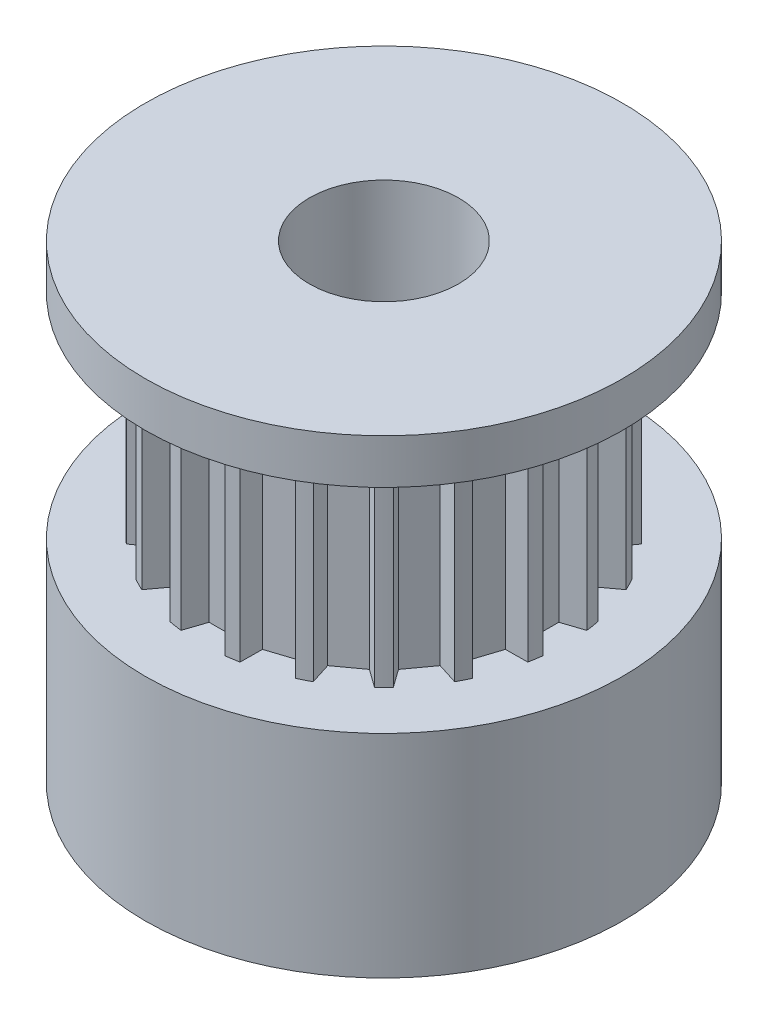
SolidWorks part; units mm, degrees
ref_plane "Front Plane" through (0, 0, 0) normal (0, 0, 1) x (1, 0, 0)
ref_plane "Top Plane" through (0, 0, 0) normal (0, 1, 0) x (1, 0, 0)
ref_plane "Right Plane" through (0, 0, 0) normal (1, 0, 0) x (0, 0, -1)
sketch "Sketch1" plane through (0, 0, 0) normal (0, 1, 0) x (1, 0, 0)
  circle A0 centre (0, 0) radius 8
extrude "Boss-Extrude1" add sketch "Sketch1" along normal blind 7.1
sketch "Sketch2" plane through (0, 7.1, 0) normal (0, 1, 0) x (1, 0, 0)
  circle A0 centre (0, 0) radius 6.11
extrude "Boss-Extrude2" add sketch "Sketch2" along normal blind 7.14
sketch "Sketch5" plane through (0, 0, 0) normal (0, -1, 0) x (1, 0, 0)
  circle A0 centre (0, 0) radius 2.5
extrude "Cut-Extrude2" cut sketch "Sketch5" against normal blind 16
sketch "Sketch7" plane through (0, 14.24, 0) normal (0, 1, 0) x (1, 0, 0)
  line L0 (0, 6.86) -> (0, 5.36) construction
  line L1 (-0.5, 5.36) -> (0.5, 5.36)
  line L2 (-1, 6.86) -> (1, 6.86)
  line L3 (-1, 6.86) -> (-0.5, 5.36)
  line L4 (1, 6.86) -> (0.5, 5.36)
  line L5 (0, 0) -> (0, 2.5) construction
  line L6 (3.0709, 6.2152) -> (2.1319, 4.9432)
  line L7 (1.1808, 5.2522) -> (2.1319, 4.9432)
  line L8 (1.1688, 6.8333) -> (1.1808, 5.2522)
  line L9 (1.1688, 6.8333) -> (3.0709, 6.2152)
  line L10 (4.8412, 4.9621) -> (3.555, 4.0424)
  line L11 (2.746, 4.6302) -> (3.555, 4.0424)
  line L12 (3.2232, 6.1376) -> (2.746, 4.6302)
  line L13 (3.2232, 6.1376) -> (4.8412, 4.9621)
  line L14 (6.1376, 3.2232) -> (4.6302, 2.746)
  line L15 (4.0424, 3.555) -> (4.6302, 2.746)
  line L16 (4.9621, 4.8412) -> (4.0424, 3.555)
  line L17 (4.9621, 4.8412) -> (6.1376, 3.2232)
  line L18 (6.8333, 1.1688) -> (5.2522, 1.1808)
  line L19 (4.9432, 2.1319) -> (5.2522, 1.1808)
  line L20 (6.2152, 3.0709) -> (4.9432, 2.1319)
  line L21 (6.2152, 3.0709) -> (6.8333, 1.1688)
  line L22 (6.86, -1) -> (5.36, -0.5)
  line L23 (5.36, 0.5) -> (5.36, -0.5)
  line L24 (6.86, 1) -> (5.36, 0.5)
  line L25 (6.86, 1) -> (6.86, -1)
  line L26 (6.2152, -3.0709) -> (4.9432, -2.1319)
  line L27 (5.2522, -1.1808) -> (4.9432, -2.1319)
  line L28 (6.8333, -1.1688) -> (5.2522, -1.1808)
  line L29 (6.8333, -1.1688) -> (6.2152, -3.0709)
  line L30 (4.9621, -4.8412) -> (4.0424, -3.555)
  line L31 (4.6302, -2.746) -> (4.0424, -3.555)
  line L32 (6.1376, -3.2232) -> (4.6302, -2.746)
  line L33 (6.1376, -3.2232) -> (4.9621, -4.8412)
  line L34 (3.2232, -6.1376) -> (2.746, -4.6302)
  line L35 (3.555, -4.0424) -> (2.746, -4.6302)
  line L36 (4.8412, -4.9621) -> (3.555, -4.0424)
  line L37 (4.8412, -4.9621) -> (3.2232, -6.1376)
  line L38 (1.1688, -6.8333) -> (1.1808, -5.2522)
  line L39 (2.1319, -4.9432) -> (1.1808, -5.2522)
  line L40 (3.0709, -6.2152) -> (2.1319, -4.9432)
  line L41 (3.0709, -6.2152) -> (1.1688, -6.8333)
  line L42 (-1, -6.86) -> (-0.5, -5.36)
  line L43 (0.5, -5.36) -> (-0.5, -5.36)
  line L44 (1, -6.86) -> (0.5, -5.36)
  line L45 (1, -6.86) -> (-1, -6.86)
  line L46 (-3.0709, -6.2152) -> (-2.1319, -4.9432)
  line L47 (-1.1808, -5.2522) -> (-2.1319, -4.9432)
  line L48 (-1.1688, -6.8333) -> (-1.1808, -5.2522)
  line L49 (-1.1688, -6.8333) -> (-3.0709, -6.2152)
  line L50 (-4.8412, -4.9621) -> (-3.555, -4.0424)
  line L51 (-2.746, -4.6302) -> (-3.555, -4.0424)
  line L52 (-3.2232, -6.1376) -> (-2.746, -4.6302)
  line L53 (-3.2232, -6.1376) -> (-4.8412, -4.9621)
  line L54 (-6.1376, -3.2232) -> (-4.6302, -2.746)
  line L55 (-4.0424, -3.555) -> (-4.6302, -2.746)
  line L56 (-4.9621, -4.8412) -> (-4.0424, -3.555)
  line L57 (-4.9621, -4.8412) -> (-6.1376, -3.2232)
  line L58 (-6.8333, -1.1688) -> (-5.2522, -1.1808)
  line L59 (-4.9432, -2.1319) -> (-5.2522, -1.1808)
  line L60 (-6.2152, -3.0709) -> (-4.9432, -2.1319)
  line L61 (-6.2152, -3.0709) -> (-6.8333, -1.1688)
  line L62 (-6.86, 1) -> (-5.36, 0.5)
  line L63 (-5.36, -0.5) -> (-5.36, 0.5)
  line L64 (-6.86, -1) -> (-5.36, -0.5)
  line L65 (-6.86, -1) -> (-6.86, 1)
  line L66 (-6.2152, 3.0709) -> (-4.9432, 2.1319)
  line L67 (-5.2522, 1.1808) -> (-4.9432, 2.1319)
  line L68 (-6.8333, 1.1688) -> (-5.2522, 1.1808)
  line L69 (-6.8333, 1.1688) -> (-6.2152, 3.0709)
  line L70 (-4.9621, 4.8412) -> (-4.0424, 3.555)
  line L71 (-4.6302, 2.746) -> (-4.0424, 3.555)
  line L72 (-6.1376, 3.2232) -> (-4.6302, 2.746)
  line L73 (-6.1376, 3.2232) -> (-4.9621, 4.8412)
  line L74 (-3.2232, 6.1376) -> (-2.746, 4.6302)
  line L75 (-3.555, 4.0424) -> (-2.746, 4.6302)
  line L76 (-4.8412, 4.9621) -> (-3.555, 4.0424)
  line L77 (-4.8412, 4.9621) -> (-3.2232, 6.1376)
  line L78 (-1.1688, 6.8333) -> (-1.1808, 5.2522)
  line L79 (-2.1319, 4.9432) -> (-1.1808, 5.2522)
  line L80 (-3.0709, 6.2152) -> (-2.1319, 4.9432)
  line L81 (-3.0709, 6.2152) -> (-1.1688, 6.8333)
  circle A0 centre (0, 0) radius 6.11 construction
  circle A2 centre (0, 0) radius 2.5 construction
  point P5 (0, 6.11)
  point P95 (0, 0)
  dimension "D1" = 2
  dimension "D2" = 1.5
  dimension "D3" = 20
extrude "Cut-Extrude3" cut sketch "Sketch7" against normal up to surface (7.14 mm away) up to face at (0, 7.1, 6.11)
sketch "Sketch8" plane through (0, 14.24, 0) normal (0, 1, 0) x (1, 0, 0)
  circle A0 centre (0, 0) radius 8
extrude "Boss-Extrude4" add sketch "Sketch8" along normal blind 1.5
sketch "Sketch9" plane through (0, 15.74, 0) normal (0, 1, 0) x (1, 0, 0)
  circle A0 centre (0, 0) radius 2.5
extrude "Cut-Extrude4" cut sketch "Sketch9" against normal up to surface (15.74 mm away) up to face at (0, 0, -2.5)
